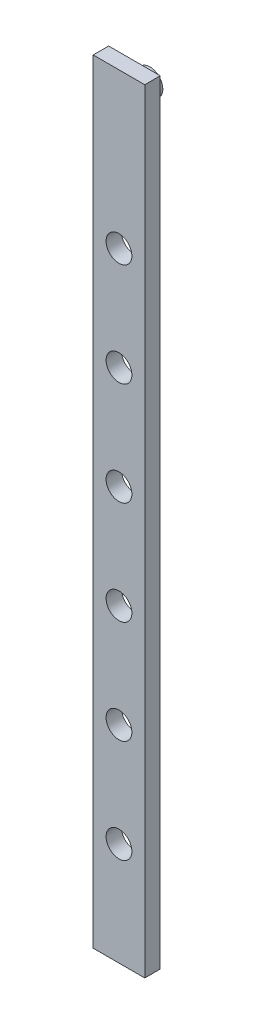
SolidWorks part; units mm, degrees
ref_plane "前基準面" through (0, 0, 0) normal (0, 0, 1) x (1, 0, 0)
ref_plane "上基準面" through (0, 0, 0) normal (0, 1, 0) x (1, 0, 0)
ref_plane "右基準面" through (0, 0, 0) normal (1, 0, 0) x (0, 0, -1)
sketch "草圖1" plane through (0, 0, 0) normal (0, 0, 1) x (1, 0, 0)
  line L0 (0, -75) -> (0, 75) construction
  line L1 (-5, -75) -> (5, -75)
  line L2 (-5, -75) -> (-5, 75)
  line L3 (-5, 75) -> (5, 75)
  line L4 (5, -75) -> (5, 75)
  line L5 (-5, -75) -> (5, 75) construction
  line L6 (-5, 75) -> (5, -75) construction
  circle A0 centre (0, -55) radius 2.5
  circle A1 centre (0, -35) radius 2.5
  circle A2 centre (0, -15) radius 2.5
  circle A3 centre (0, 5) radius 2.5
  circle A4 centre (0, 25) radius 2.5
  circle A5 centre (0, 45) radius 2.5
  point P0 (0, 0)
  dimension "D3" = 20
  dimension "D9" = 5
  dimension "D1" = 150
  dimension "D2" = 10
  dimension "D4" = 20
  dimension "D5" = 20
  dimension "D6" = 20
  dimension "D7" = 20
  dimension "D8" = 20
extrude "填料-伸長1" add sketch "草圖1" along normal blind 3
sketch "草圖2" plane through (0, 0, 3) normal (0, 0, 1) x (1, 0, 0)
  line L1 (5, 75) -> (-5, 75) construction
  circle A0 centre (0, 70) radius 2.5
  dimension "D1" = 5
  dimension "D2" = 5
extrude "填料-伸長2" add sketch "草圖2" against normal blind 6
